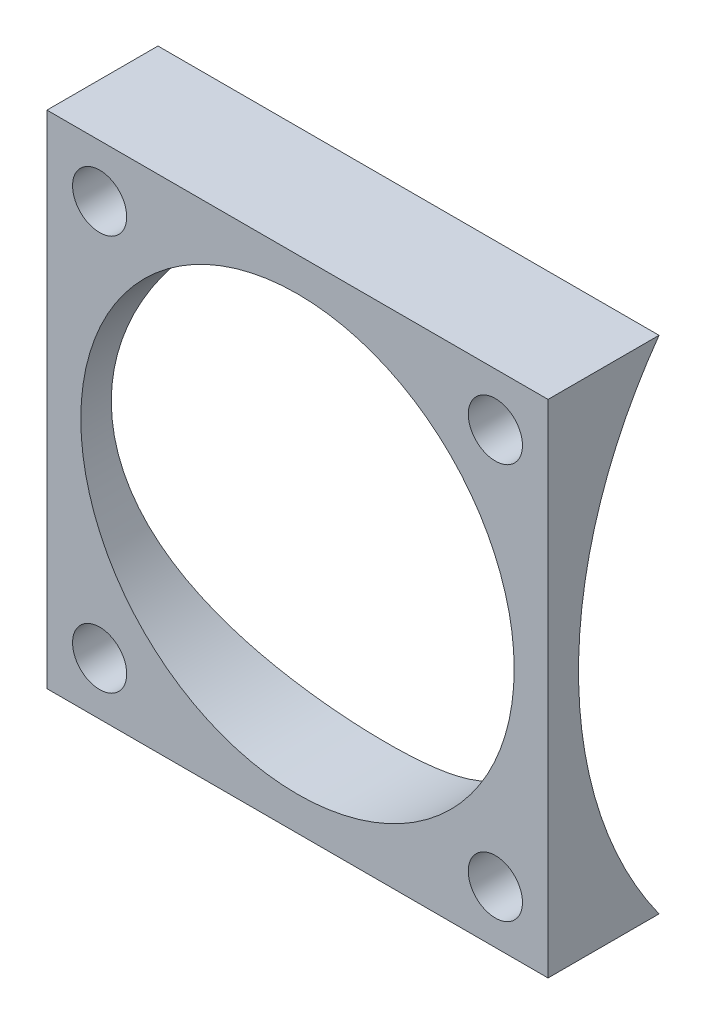
SolidWorks part; units mm, degrees
ref_plane "Front Plane" through (0, 0, 0) normal (0, 0, 1) x (1, 0, 0)
ref_plane "Top Plane" through (0, 0, 0) normal (0, 1, 0) x (1, 0, 0)
ref_plane "Right Plane" through (0, 0, 0) normal (1, 0, 0) x (0, 0, -1)
sketch "Sketch1" plane through (0, 0, 0) normal (0, 0, 1) x (1, 0, 0)
  line L1 (-18.5, 18.5) -> (18.5, 18.5)
  line L2 (-18.5, 18.5) -> (-18.5, -18.5)
  line L3 (-18.5, -18.5) -> (18.5, -18.5)
  line L4 (18.5, 18.5) -> (18.5, -18.5)
  line L5 (-18.5, 18.5) -> (18.5, -18.5) construction
  line L6 (-18.5, -18.5) -> (18.5, 18.5) construction
  point P0 (0, 0)
  dimension "D1" = 37
  dimension "D2" = 37
extrude "Boss-Extrude1" add sketch "Sketch1" along normal blind 34
sketch "Sketch2" plane through (0, 0, 0) normal (1, 0, 0) x (0, 0, -1)
  circle A0 centre (0, 0) radius 31.75
  dimension "D1" = 63.5
extrude "Cut-Extrude1" cut sketch "Sketch2" against normal blind 20 and the other way blind 20
sketch "Sketch5" plane through (0, 0, 0) normal (0, 0, 1) x (1, 0, 0)
  circle A0 centre (0, 0) radius 16
  dimension "D1" = 32
extrude "Cut-Extrude2" cut sketch "Sketch5" along normal through all
sketch "Sketch6" plane through (0, 0, 34) normal (0, 0, 1) x (1, 0, 0)
  line L0 (-18.5, 18.5) -> (18.5, -18.5) construction
  line L1 (18.5, -18.5) -> (-18.5, -18.5) construction
  line L2 (-18.5, -18.5) -> (18.5, 18.5) construction
  circle A1 centre (-14.6109, -14.6109) radius 2
  circle A2 centre (14.6109, -14.6109) radius 2
  circle A3 centre (14.6109, 14.6109) radius 2
  circle A4 centre (-14.6109, 14.6109) radius 2
  point P4 (-14.6109, 14.6109)
  point P9 (14.6109, 14.6109)
  point P10 (-14.6109, -14.6109)
  point P11 (14.6109, -14.6109)
  dimension "D5" = 4
  dimension "D6" = 4
  dimension "D7" = 4
  dimension "D8" = 4
  dimension "D1" = 5.5
  dimension "D2" = 5.5
  dimension "D3" = 5.5
  dimension "D4" = 5.5
extrude "Cut-Extrude3" cut sketch "Sketch6" against normal through all
